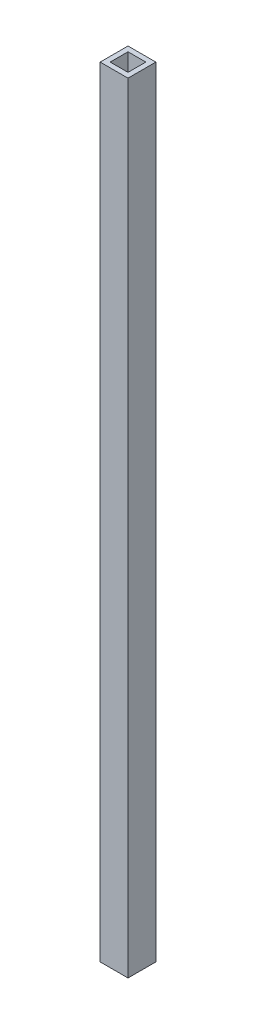
SolidWorks part; units mm, degrees
ref_plane "前视基准面" through (0, 0, 0) normal (0, 0, 1) x (1, 0, 0)
ref_plane "上视基准面" through (0, 0, 0) normal (0, 1, 0) x (1, 0, 0)
ref_plane "右视基准面" through (0, 0, 0) normal (1, 0, 0) x (0, 0, -1)
sketch "草图1" plane through (0, 0, 0) normal (0, 1, 0) x (1, 0, 0)
  line L1 (-5, 5) -> (5, 5)
  line L2 (-5, 5) -> (-5, -5)
  line L3 (-5, -5) -> (5, -5)
  line L4 (5, 5) -> (5, -5)
  line L5 (-5, 5) -> (5, -5) construction
  line L6 (-5, -5) -> (5, 5) construction
  line L7 (-3.2, 3.2) -> (3.2, 3.2)
  line L8 (-3.2, 3.2) -> (-3.2, -3.2)
  line L9 (-3.2, -3.2) -> (3.2, -3.2)
  line L10 (3.2, 3.2) -> (3.2, -3.2)
  line L11 (-3.2, 3.2) -> (3.2, -3.2) construction
  line L12 (-3.2, -3.2) -> (3.2, 3.2) construction
  point P0 (0, 0)
  point P6 (0, 0)
  dimension "D1" = 1.8
  dimension "D2" = 10
extrude "凸台-拉伸1" add sketch "草图1" along normal blind 280
